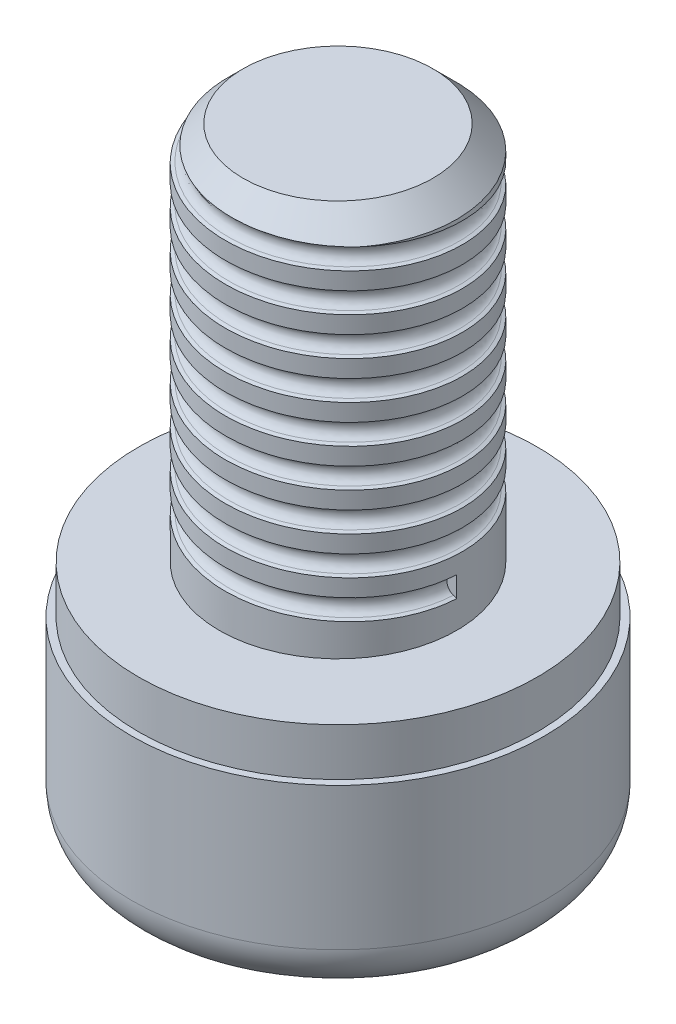
SolidWorks part; units mm, degrees
ref_plane "Спереди" through (0, 0, 0) normal (0, 0, 1) x (1, 0, 0)
ref_plane "Сверху" through (0, 0, 0) normal (0, 1, 0) x (1, 0, 0)
ref_plane "Справа" through (0, 0, 0) normal (1, 0, 0) x (0, 0, -1)
sketch "Эскиз1" plane through (0, 0, 0) normal (0, 1, 0) x (1, 0, 0)
  circle A0 centre (0, 0) radius 4.35
  dimension "D1" = 8.7
extrude "Бобышка-Вытянуть1" add sketch "Эскиз1" along normal blind 5
sketch "Эскиз2" plane through (0, 5, 0) normal (0, 1, 0) x (1, 0, 0)
  circle A0 centre (0, 0) radius 2.5
  dimension "D1" = 5
extrude "Бобышка-Вытянуть2" add sketch "Эскиз2" along normal blind 8
chamfer "Фаска1" distance 0.5 angle 45 1 edges at (0, 13, 2.5)
sketch "Эскиз3" plane through (0, 0, 0) normal (0, -1, 0) x (1, 0, 0)
  line L1 (1.9892, -1.1731) -> (2.0106, 1.1362)
  line L2 (2.0106, 1.1362) -> (0.0214, 2.3093)
  line L3 (0.0214, 2.3093) -> (-1.9892, 1.1731)
  line L4 (-1.9892, 1.1731) -> (-2.0106, -1.1362)
  line L5 (-2.0106, -1.1362) -> (-0.0214, -2.3093)
  line L6 (-0.0214, -2.3093) -> (1.9892, -1.1731)
  circle A0 centre (0, 0) radius 2 construction
  dimension "D1" = 4
extrude "Вырез-Вытянуть1" cut sketch "Эскиз3" against normal blind 2.5
fillet "Скругление1" radius 1 1 edges at (0, 0, 4.35)
sketch "Эскиз4" plane through (0, 5, 0) normal (0, 1, 0) x (1, 0, 0)
  circle A0 centre (0, 0) radius 4.2
  circle A1 centre (0, 0) radius 4.35
  dimension "D1" = 8.4
extrude "Вырез-Вытянуть3" cut sketch "Эскиз4" against normal blind 1
sketch "Эскиз7" plane through (0, 13, 0) normal (0, 1, 0) x (1, 0, 0)
  circle A0 centre (0, 0) radius 2.5
ref_plane "Плоскость2" through (0, 12.5, 0) normal (0, -1, 0) x (-1, 0, 0)
sketch "Эскиз8" plane through (0, 12.5, 0) normal (0, -1, 0) x (-1, 0, 0)
  circle A0 centre (0, 0) radius 2.5
curve "Спираль2" pitch 0.8 height 7.2 turns 9
sketch "Эскиз10" plane through (0, 0, 0) normal (0, 0, 1) x (1, 0, 0)
  line L0 (2.9, 13.364) -> (2.9, 12.636)
  line L1 (2.9, 12.636) -> (2.4298, 12.8072)
  line L2 (2.4298, 13.1928) -> (2.9, 13.364)
  line L3 (2.9, 13) -> (2.2948, 13) construction
  arc A0 (2.4298, 13.1928) -> (2.4298, 12.8072) centre (2.5, 13) ccw
  dimension "D1" = 40
  dimension "D2" = 0.4702
  dimension "D3" = 0.4
  dimension "D4" = 2.9
sweep "Вырез-По траектории1" cut profiles "Эскиз10" path "Спираль2"
